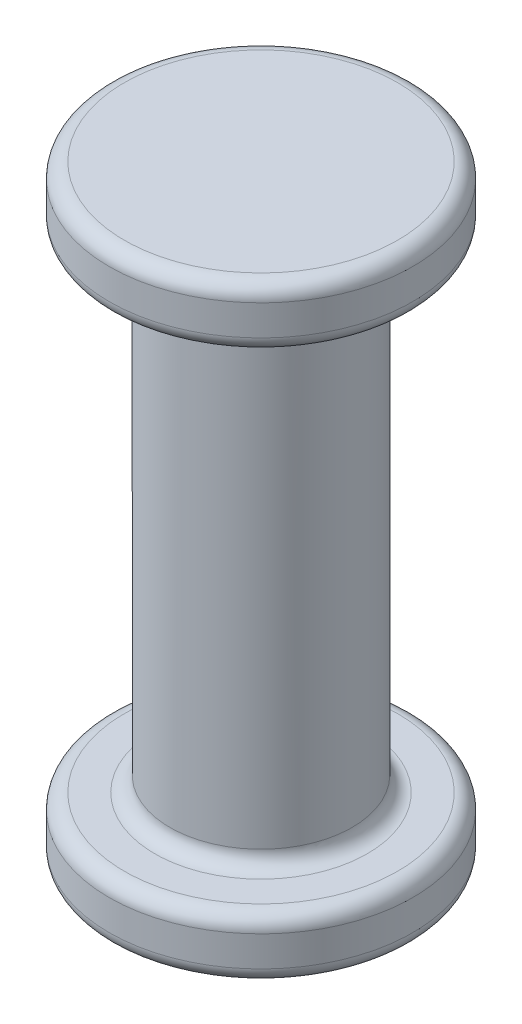
SolidWorks part; units mm, degrees
material "Chrome Stainless Steel"
ref_plane "Front Plane" through (0, 0, 0) normal (0, 0, 1) x (1, 0, 0)
ref_plane "Top Plane" through (0, 0, 0) normal (0, 1, 0) x (1, 0, 0)
ref_plane "Right Plane" through (0, 0, 0) normal (1, 0, 0) x (0, 0, -1)
sketch "Sketch2" plane through (0, 0, 0) normal (0, 0, 1) x (1, 0, 0)
  line L0 (0, 0) -> (0, 10)
  line L1 (0, 10) -> (-2.5, 10)
  line L2 (-2.5, 10) -> (-2.5, 9)
  line L3 (-2.5, 9) -> (-1.5, 9)
  line L4 (-1.5, 9) -> (-1.5, 1)
  line L5 (-1.5, 1) -> (-2.5, 1)
  line L6 (-2.5, 1) -> (-2.5, 0)
  line L7 (-2.5, 0) -> (0, 0)
  dimension "D1" = 10
  dimension "D2" = 2.5
  dimension "D3" = 1.5
  dimension "D4" = 1
revolve "Revolve1" add sketch "Sketch2" angle 360 about L0
fillet "Fillet1" radius 0.25 6 edges at (0, 10, -2.5) (0, 9, -2.5) (0, 9, -1.5) (0, 1, -1.5) (0, 1, -2.5) (0, 0, -2.5)
